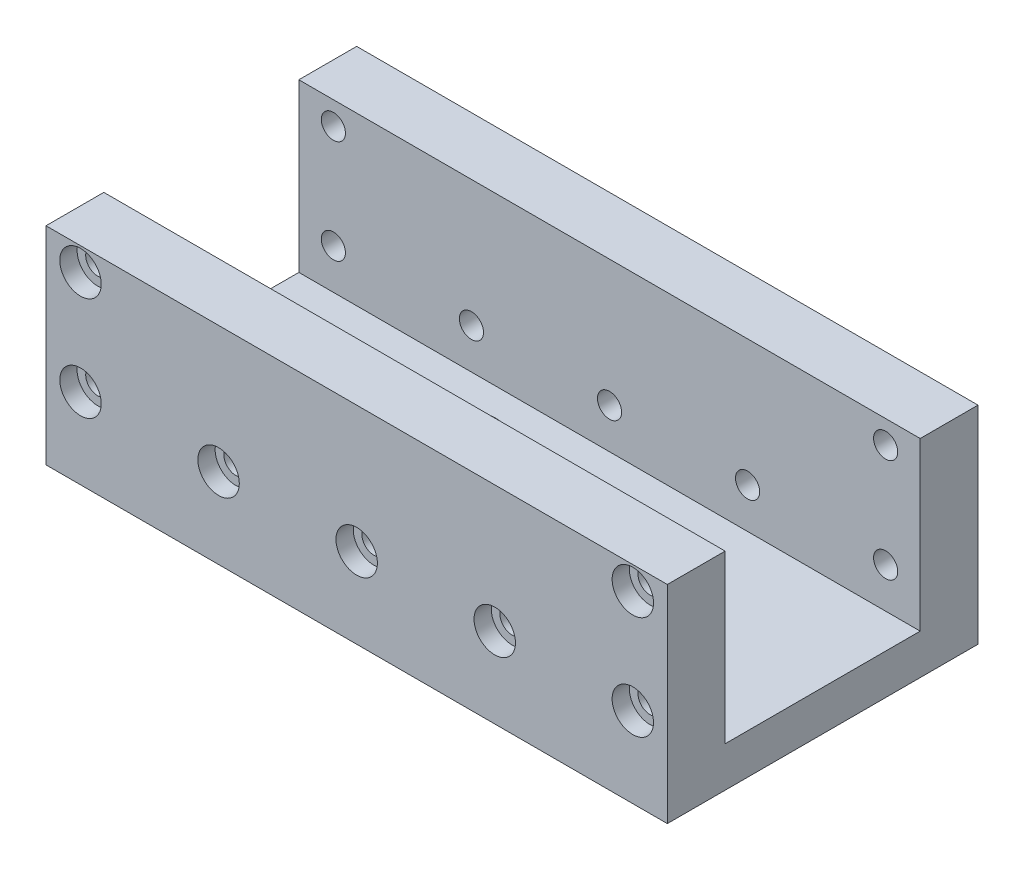
SolidWorks part; units mm, degrees
ref_plane "Front Plane" through (0, 0, 0) normal (0, 0, 1) x (1, 0, 0)
ref_plane "Top Plane" through (0, 0, 0) normal (0, 1, 0) x (1, 0, 0)
ref_plane "Right Plane" through (0, 0, 0) normal (1, 0, 0) x (0, 0, -1)
sketch "Sketch1" plane through (0, 0, 0) normal (0, 1, 0) x (1, 0, 0)
  line L1 (-54, 27) -> (54, 27)
  line L2 (-54, 27) -> (-54, -27)
  line L3 (-54, -27) -> (54, -27)
  line L4 (54, 27) -> (54, -27)
  dimension "D1" = 27
  dimension "D2" = 54
  dimension "D3" = 108
  dimension "D4" = 54
extrude "Boss-Extrude1" add sketch "Sketch1" along normal blind 6
sketch "Sketch2" plane through (0, 6, 0) normal (0, 1, 0) x (1, 0, 0)
  circle A0 centre (-14.9389, 8.625) radius 2
  circle A1 centre (-14.9389, -8.625) radius 2
  circle A2 centre (15.3856, 7.8004) radius 2
  circle A3 centre (15.3856, -8.625) radius 2
  dimension "D1" = 17.25
  dimension "D2" = 8.625
  dimension "D4" = 8.625
  dimension "D5" = 17.25
  dimension "D3" = 17.25
extrude "Cut-Extrude1" cut sketch "Sketch2" against normal blind 12
sketch "Sketch3" plane through (0, 6, 0) normal (0, 1, 0) x (1, 0, 0)
  circle A0 centre (-14.9389, 8.625) radius 3.5
  circle A1 centre (-14.9389, -8.625) radius 3.5
  circle A2 centre (15.3856, 7.8004) radius 3.5
  circle A3 centre (15.3856, -8.625) radius 3.5
extrude "Cut-Extrude3" cut sketch "Sketch3" against normal blind 4
sketch "Sketch4" plane through (0, 6, 0) normal (0, 1, 0) x (1, 0, 0)
  line L0 (-54, 27) -> (-54, -27) construction
  line L1 (-54, 27) -> (54, 27)
  line L2 (-54, 27) -> (-54, -27)
  line L3 (-54, -27) -> (54, -27)
  line L4 (54, 27) -> (54, -27)
  line L5 (54, -27) -> (54, 27) construction
  dimension "D1" = 27
  dimension "D2" = 54
extrude "Boss-Extrude2" add sketch "Sketch4" along normal blind 30
sketch "Sketch5" plane through (0, 36, 0) normal (0, 1, 0) x (1, 0, 0)
  line L0 (-54, 27) -> (-54, -27) construction
  line L1 (-54, 16.95) -> (54, 16.95)
  line L2 (-54, 16.95) -> (-54, -16.95)
  line L3 (-54, -16.95) -> (54, -16.95)
  line L4 (54, 16.95) -> (54, -16.95)
  line L5 (54, -27) -> (54, 27) construction
  dimension "D1" = 33.9
  dimension "D2" = 16.95
extrude "Cut-Extrude4" cut sketch "Sketch5" against normal blind 29 contours L1 L4 L3 L2
sketch "Sketch6" plane through (0, 0, 27) normal (0, 0, 1) x (1, 0, 0)
  line L0 (-54, 0) -> (54, 0) construction
  circle A0 centre (0, 14) radius 2.1
  circle A1 centre (-24, 14) radius 2.1
  circle A2 centre (-48, 14) radius 2.1
  circle A3 centre (24, 14) radius 2.1
  circle A4 centre (48, 14) radius 2.1
  circle A5 centre (48, 32) radius 2.1
  circle A6 centre (-48, 32) radius 2.1
  dimension "D1" = 14
  dimension "D2" = 24
  dimension "D3" = 24
  dimension "D4" = 24
  dimension "D5" = 24
  dimension "D6" = 18
  dimension "D7" = 18
extrude "Cut-Extrude5" cut sketch "Sketch6" against normal blind 67
sketch "Sketch7" plane through (0, 0, 27) normal (0, 0, 1) x (1, 0, 0)
  circle A0 centre (-48, 32) radius 3.6
  circle A1 centre (-48, 14) radius 3.6
  circle A2 centre (-24, 14) radius 3.6
  circle A3 centre (0, 14) radius 3.6
  circle A4 centre (24, 14) radius 3.6
  circle A5 centre (48, 14) radius 3.6
  circle A6 centre (48, 32) radius 3.6
extrude "Cut-Extrude6" cut sketch "Sketch7" against normal blind 3
sketch "Sketch8" plane through (0, 0, -27) normal (0, 0, -1) x (-1, 0, 0)
  line L45 (-50.0207, 28.5) -> (-45.9793, 28.5)
  line L46 (-45.9793, 28.5) -> (-43.9585, 32)
  line L47 (-43.9585, 32) -> (-45.9793, 35.5)
  line L48 (-45.9793, 35.5) -> (-50.0207, 35.5)
  line L49 (-50.0207, 35.5) -> (-52.0415, 32)
  line L50 (-52.0415, 32) -> (-50.0207, 28.5)
  line L51 (-50.0207, 10.5) -> (-45.9793, 10.5)
  line L52 (-45.9793, 10.5) -> (-43.9585, 14)
  line L53 (-43.9585, 14) -> (-45.9793, 17.5)
  line L54 (-45.9793, 17.5) -> (-50.0207, 17.5)
  line L55 (-50.0207, 17.5) -> (-52.0415, 14)
  line L56 (-52.0415, 14) -> (-50.0207, 10.5)
  line L57 (-26.0207, 10.5) -> (-21.9793, 10.5)
  line L58 (-21.9793, 10.5) -> (-19.9585, 14)
  line L59 (-19.9585, 14) -> (-21.9793, 17.5)
  line L60 (-21.9793, 17.5) -> (-26.0207, 17.5)
  line L61 (-26.0207, 17.5) -> (-28.0415, 14)
  line L62 (-28.0415, 14) -> (-26.0207, 10.5)
  line L63 (-2.0207, 10.5) -> (2.0207, 10.5)
  line L64 (2.0207, 10.5) -> (4.0415, 14)
  line L65 (4.0415, 14) -> (2.0207, 17.5)
  line L66 (2.0207, 17.5) -> (-2.0207, 17.5)
  line L67 (-2.0207, 17.5) -> (-4.0415, 14)
  line L68 (-4.0415, 14) -> (-2.0207, 10.5)
  line L69 (21.9793, 10.5) -> (26.0207, 10.5)
  line L70 (26.0207, 10.5) -> (28.0415, 14)
  line L71 (28.0415, 14) -> (26.0207, 17.5)
  line L72 (26.0207, 17.5) -> (21.9793, 17.5)
  line L73 (21.9793, 17.5) -> (19.9585, 14)
  line L74 (19.9585, 14) -> (21.9793, 10.5)
  line L75 (45.9793, 10.5) -> (50.0207, 10.5)
  line L76 (50.0207, 10.5) -> (52.0415, 14)
  line L77 (52.0415, 14) -> (50.0207, 17.5)
  line L78 (50.0207, 17.5) -> (45.9793, 17.5)
  line L79 (45.9793, 17.5) -> (43.9585, 14)
  line L80 (43.9585, 14) -> (45.9793, 10.5)
  line L81 (45.9793, 28.5) -> (50.0207, 28.5)
  line L82 (50.0207, 28.5) -> (52.0415, 32)
  line L83 (52.0415, 32) -> (50.0207, 35.5)
  line L84 (50.0207, 35.5) -> (45.9793, 35.5)
  line L85 (45.9793, 35.5) -> (43.9585, 32)
  line L86 (43.9585, 32) -> (45.9793, 28.5)
  circle A0 centre (-48, 32) radius 3.5 construction
  circle A1 centre (-48, 14) radius 3.5 construction
  circle A2 centre (-24, 14) radius 3.5 construction
  circle A3 centre (0, 14) radius 3.5 construction
  circle A4 centre (24, 14) radius 3.5 construction
  circle A5 centre (48, 14) radius 3.5 construction
  circle A6 centre (48, 32) radius 3.5 construction
extrude "Cut-Extrude7" cut sketch "Sketch8" against normal blind 3
sketch "Sketch10" plane through (0, 6, 0) normal (0, -1, 0) x (1, 0, 0)
  circle A0 centre (-14.9389, -8.625) radius 3.5
  circle A1 centre (-14.9389, 8.625) radius 3.5
  circle A2 centre (15.3856, 8.625) radius 3.5
  circle A3 centre (15.3856, -7.8004) radius 3.5
extrude "Cut-Extrude8" cut sketch "Sketch10" against normal blind 3
sketch "Sketch11" plane through (0, 7, 0) normal (0, 1, 0) x (1, 0, 0)
  circle A0 centre (0, 0) radius 4
extrude "Cut-Extrude9" cut sketch "Sketch11" against normal blind 10 contours A0
